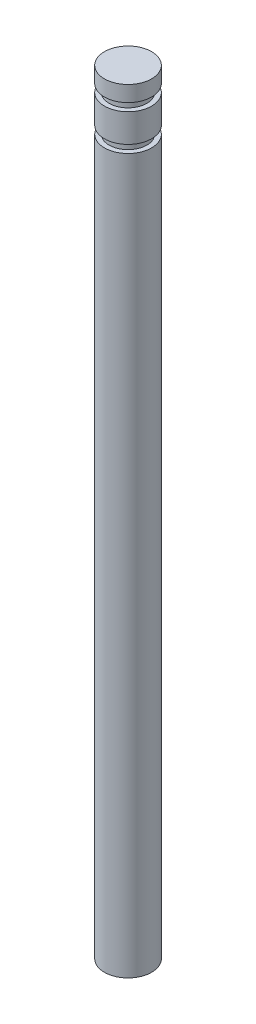
SolidWorks part; units mm, degrees
material "Простая углеродистая сталь"
ref_plane "Спереди" through (0, 0, 0) normal (0, 0, 1) x (1, 0, 0)
ref_plane "Сверху" through (0, 0, 0) normal (0, 1, 0) x (1, 0, 0)
ref_plane "Справа" through (0, 0, 0) normal (1, 0, 0) x (0, 0, -1)
sketch "Эскиз2" plane through (0, 0, 0) normal (1, 0, 0) x (0, 0, -1)
  line L1 (0, 0) -> (1.5, 0)
  line L2 (0, 0) -> (0, 49.2)
  line L3 (0, 49.2) -> (1.5, 49.2)
  line L4 (1.5, 0) -> (1.5, 49.2)
  line L5 (1.5, 48.2) -> (1.2, 48.2)
  line L6 (1.5, 48.2) -> (1.5, 47.7)
  line L7 (1.5, 47.7) -> (1.2, 47.7)
  line L8 (1.2, 48.2) -> (1.2, 47.7)
  line L9 (1.5, 45.9) -> (1.2, 45.9)
  line L10 (1.5, 45.9) -> (1.5, 45.4)
  line L11 (1.5, 45.4) -> (1.2, 45.4)
  line L12 (1.2, 45.9) -> (1.2, 45.4)
  dimension "D1" = 1.5
  dimension "D2" = 49.2
  dimension "D3" = 0.5
  dimension "D4" = 0.3
  dimension "D5" = 1
  dimension "D6" = 3.3
revolve "Повернуть1" add sketch "Эскиз2" angle 360 about L2
cosmetic thread "Условное изображение резьбы1" parameters "D1"=7, "D2"=2.439
